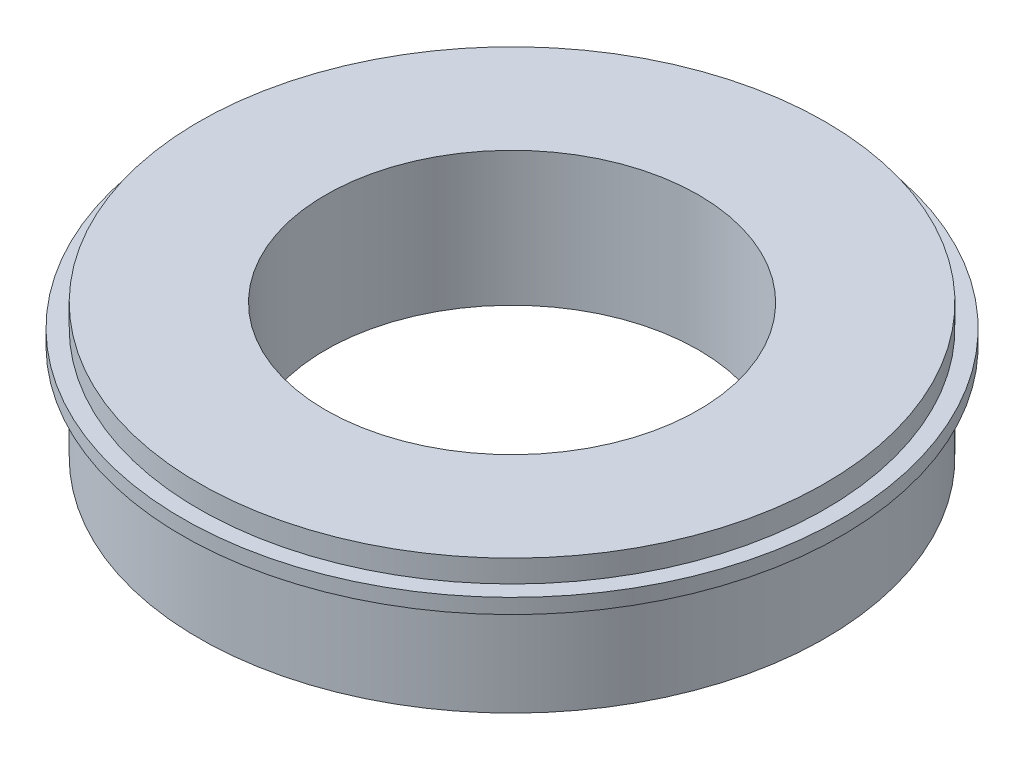
SolidWorks part; units mm, degrees
ref_plane "Alzado" through (0, 0, 0) normal (0, 0, 1) x (1, 0, 0)
ref_plane "Planta" through (0, 0, 0) normal (0, 1, 0) x (1, 0, 0)
ref_plane "Vista lateral" through (0, 0, 0) normal (1, 0, 0) x (0, 0, -1)
sketch "Croquis1" plane through (0, 0, 0) normal (0, 0, 1) x (1, 0, 0)
  line L0 (0, 0) -> (0, 15.0728) construction
  line L1 (21, 7.5) -> (21, 9)
  line L2 (12.5, 0) -> (21, 0)
  line L3 (12.5, 0) -> (12.5, 9)
  line L4 (12.5, 9) -> (21, 9)
  line L5 (21, 0) -> (21, 6.5)
  line L6 (21, 6.5) -> (22.1, 6.5)
  line L8 (21, 7.5) -> (22.1, 7.5)
  line L9 (22.1, 6.5) -> (22.1, 7.5)
  dimension "D1" = 42
  dimension "D2" = 25
  dimension "D3" = 9
  dimension "D4" = 6.5
  dimension "D5" = 1
  dimension "D6" = 1.1
revolve "Revolución1" add sketch "Croquis1" angle 360 about L0
